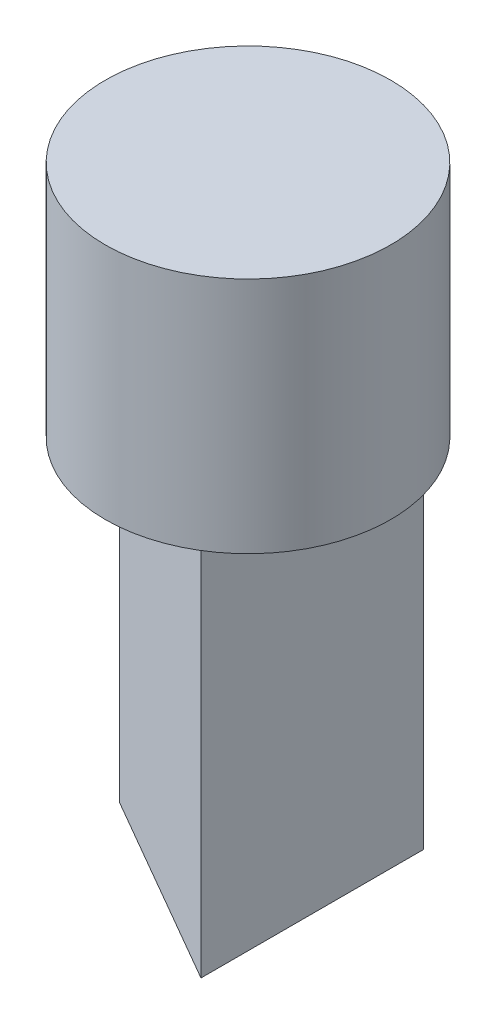
SolidWorks part; units mm, degrees
ref_plane "Front" through (0, 0, 0) normal (0, 0, 1) x (1, 0, 0)
ref_plane "Top" through (0, 0, 0) normal (0, 1, 0) x (1, 0, 0)
ref_plane "Right" through (0, 0, 0) normal (1, 0, 0) x (0, 0, -1)
sketch "Sketch1" plane through (0, 0, 0) normal (0, 1, 0) x (1, 0, 0)
  circle A0 centre (0, 0) radius 3
  dimension "D1" = 6
extrude "Boss-Extrude1" add sketch "Sketch1" along normal blind 5
sketch "Sketch2" plane through (0, 0, 0) normal (0, -1, 0) x (1, 0, 0)
  line L0 (-2.7, 0) -> (1.35, -2.3383)
  line L1 (1.35, -2.3383) -> (1.35, 2.3383)
  line L2 (1.35, 2.3383) -> (-2.7, 0)
  circle A0 centre (0, 0) radius 2.7
  dimension "D1" = 5.4
  dimension "D2" = 60
extrude "Boss-Extrude2" add sketch "Sketch2" along normal blind 8 contours L1 L2 L0
